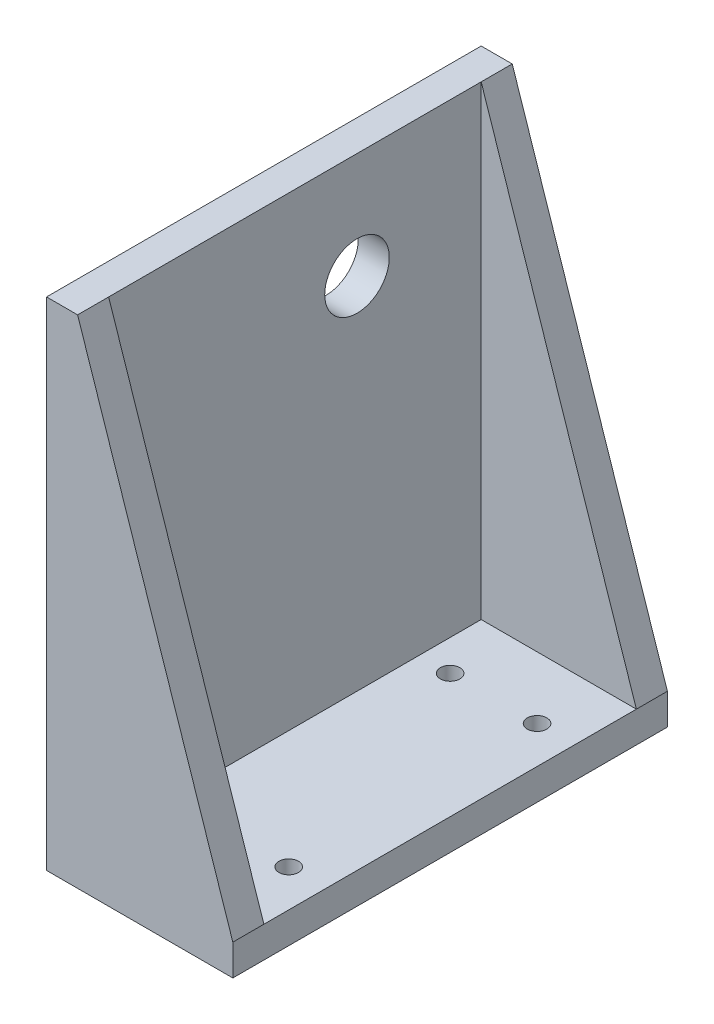
SolidWorks part; units mm, degrees
ref_plane "Front Plane" through (0, 0, 0) normal (0, 0, 1) x (1, 0, 0)
ref_plane "Top Plane" through (0, 0, 0) normal (0, 1, 0) x (1, 0, 0)
ref_plane "Right Plane" through (0, 0, 0) normal (1, 0, 0) x (0, 0, -1)
sketch "Sketch1" plane through (0, 0, 0) normal (0, 0, 1) x (1, 0, 0)
  line L0 (0, 0) -> (0, 50.8)
  line L1 (0, 50.8) -> (3.175, 50.8)
  line L2 (3.175, 50.8) -> (3.175, 3.175)
  line L3 (3.175, 3.175) -> (19.05, 3.175)
  line L4 (19.05, 3.175) -> (19.05, 0)
  line L5 (19.05, 0) -> (0, 0)
  point P3 (3.8, 3.175)
  dimension "D1" = 3.175
  dimension "D2" = 3.175
  dimension "D3" = 19.05
  dimension "D4" = 50.8
extrude "Boss-Extrude1" add sketch "Sketch1" along normal mid plane 44.45
sketch "Sketch2" plane through (0, 0, 0) normal (-1, 0, 0) x (0, 0, 1)
  line L1 (22.225, 50.8) -> (22.225, 0) construction
  line L2 (22.225, 0) -> (-22.225, 0) construction
  circle A0 centre (-6.35, 39.9542) radius 3.302
  dimension "D3" = 6.604
  dimension "D1" = 28.575
  dimension "D2" = 39.9542
sketch "Sketch3" plane through (0, 0, 22.225) normal (0, 0, 1) x (1, 0, 0)
  line L0 (3.175, 50.8) -> (19.05, 3.175)
  line L1 (19.05, 3.175) -> (3.175, 3.175)
  line L2 (3.175, 3.175) -> (3.175, 50.8)
extrude "Cut-Extrude1" cut sketch "Sketch2" against normal through all
extrude "Boss-Extrude2" add sketch "Sketch3" against normal blind 3.175
mirror "Mirror1" about plane through (0, 0, 0) normal (0, 0, 1) of "Boss-Extrude2"
sketch "Sketch4" plane through (0, 3.175, 0) normal (0, 1, 0) x (1, 0, 0)
  line L1 (3.175, 19.05) -> (19.05, 19.05) construction
  line L3 (3.175, 0) -> (19.05, 0) construction
  line L4 (3.175, -19.05) -> (3.175, 19.05) construction
  line L5 (19.05, -19.05) -> (19.05, 19.05) construction
  circle A0 centre (6.35, 12.7) radius 1
  circle A1 centre (15.24, 12.7) radius 1
  circle A2 centre (15.24, -12.7) radius 1
  circle A3 centre (6.35, -12.7) radius 1
  dimension "D1" = 2
  dimension "D2" = 6.35
  dimension "D3" = 3.175
  dimension "D5" = 8.89
  dimension "D4" = 2
extrude "Cut-Extrude2" cut sketch "Sketch4" against normal through all
equation "\"D1@Sketch4\"=2mm"
equation "\"tightTol\" = 0.005in"
equation "\"normTol\"= 0.01in"
equation "\"looseTol\"= 0.02in"
equation "\"D3@Sketch2\"=\"normTol\"+1/4"
